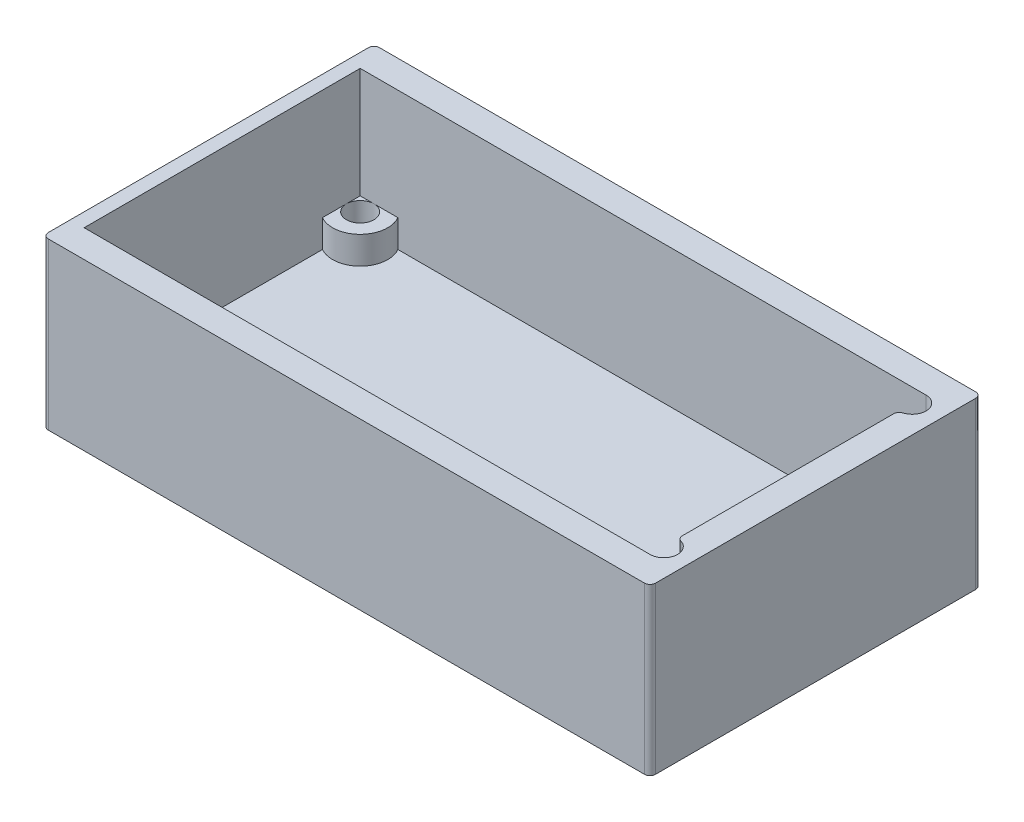
SolidWorks part; units mm, degrees
ref_plane "Front Plane" through (0, 0, 0) normal (0, 0, 1) x (1, 0, 0)
ref_plane "Top Plane" through (0, 0, 0) normal (0, 1, 0) x (1, 0, 0)
ref_plane "Right Plane" through (0, 0, 0) normal (1, 0, 0) x (0, 0, -1)
sketch "Sketch1" plane through (0, 0, 0) normal (0, 1, 0) x (1, 0, 0)
  line L1 (-11, -6) -> (11, -6)
  line L2 (-11, -6) -> (-11, 6)
  line L3 (-11, 6) -> (11, 6)
  line L4 (11, -6) -> (11, 6)
  line L5 (-11, -6) -> (11, 6) construction
  line L6 (-11, 6) -> (11, -6) construction
  point P0 (0, 0)
  dimension "D1" = 12
  dimension "D2" = 22
extrude "Boss-Extrude1" add sketch "Sketch1" along normal blind 6
fillet "Fillet1" radius 0.2 4 edges at (-11, 3, -6) (11, 3, -6) (11, 3, 6) (-11, 3, 6)
sketch "Sketch2" plane through (0, 6, 0) normal (0, 1, 0) x (1, 0, 0)
  line L0 (11, -5.8) -> (11, 5.8) construction
  line L1 (-10.5, -5) -> (10, -5)
  line L2 (-10.5, -5) -> (-10.5, 5)
  line L3 (-10.5, 5) -> (10, 5)
  line L4 (10, -5) -> (10, 5)
  line L5 (-10.5, -5) -> (10, 5) construction
  line L6 (-10.5, 5) -> (10, -5) construction
  line L7 (10.8, 6) -> (-10.8, 6) construction
  line L8 (-10.8, -6) -> (10.8, -6) construction
  line L9 (-11, 5.8) -> (-11, -5.8) construction
  point P0 (-0.25, 0)
  dimension "D1" = 10
  dimension "D2" = 20.5
  dimension "D3" = 1
  dimension "D4" = 1
  dimension "D5" = 1
  dimension "D6" = 0.5
extrude "Cut-Extrude1" cut sketch "Sketch2" against normal blind 5
sketch "Sketch3" plane through (0, 1, 0) normal (0, 1, 0) x (1, 0, 0)
  circle A0 centre (10, 4.5) radius 1
  circle A1 centre (10, 4.5) radius 0.5
extrude "Boss-Extrude2" add sketch "Sketch3" along normal blind 1
mirror "Mirror1" about plane through (0, 0, 0) normal (0, 0, 1) of "Boss-Extrude2"
sketch "Sketch7" plane through (0, 1, 0) normal (0, 1, 0) x (1, 0, 0)
  circle A0 centre (-10, 4.5) radius 1
  circle A1 centre (-10, 4.5) radius 0.5
extrude "Boss-Extrude3" add sketch "Sketch7" along normal blind 1
mirror "Mirror3" about plane through (0, 0, 0) normal (0, 0, 1) of "Boss-Extrude3"
sketch "Sketch8" plane through (0, 6, 0) normal (0, 1, 0) x (1, 0, 0)
  line L0 (10, 4) -> (10, 5) construction
  circle A0 centre (10, 4.5) radius 0.5
extrude "Cut-Extrude4" cut sketch "Sketch8" against normal through all
mirror "Mirror4" about plane through (0, 0, 0) normal (0, 0, 1) of "Cut-Extrude4"
fillet "Fillet2" radius 0.2 2 edges at (10, 4, 4) (10, 4, -4)
mirror "Mirror5" about plane through (0, 0, 0) normal (1, 0, 0) of "Mirror4", "Cut-Extrude4"
sketch "Sketch9" plane through (0, 0, 0) normal (0, -1, 0) x (-1, 0, 0)
  circle A0 centre (-10, -4.5) radius 0.9
extrude "Cut-Extrude12" cut sketch "Sketch9" against normal blind 1
mirror "Mirror6" about plane through (0, 0, 0) normal (1, 0, 0) of "Cut-Extrude12"
mirror "Mirror7" about plane through (0, 0, 0) normal (0, 0, 1) of "Mirror6", "Cut-Extrude12"
